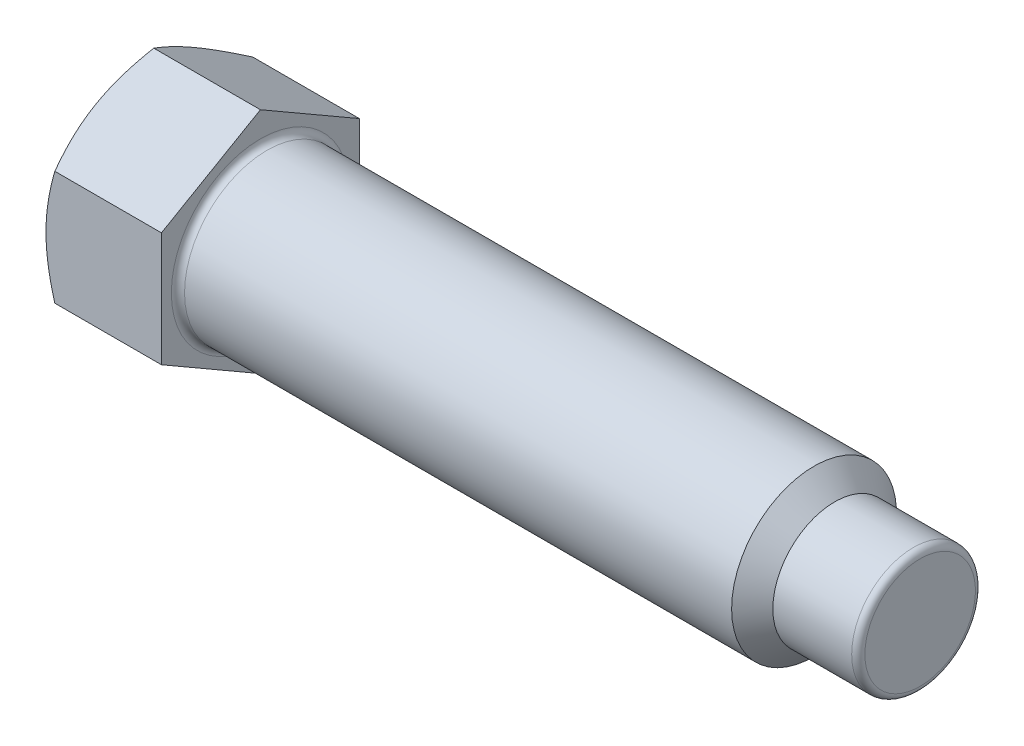
SolidWorks part; units mm, degrees
extrude "BaseHead" add sketch "HexSke" along normal blind 14
sketch "HexSke" plane through (0, 0, 0) normal (1, 0, 0) x (0, 0, -1)
  line L0 (12, 6.9282) -> (12, -6.9282)
  line L1 (-12, 6.9282) -> (-12, -6.9282)
  line L2 (12, -6.9282) -> (0, -13.8564)
  line L3 (0, -13.8564) -> (-12, -6.9282)
  line L4 (12, 6.9282) -> (0, 13.8564)
  line L5 (0, 13.8564) -> (-12, 6.9282)
  dimension "Width_flats" = 24
  dimension "D2" = 120
  dimension "D3" = 12
  dimension "D4" = 12
  dimension "D5" = 12
ref_plane "Plane1" through (0, 0, 0) normal (0, 0, 1) x (1, 0, 0)
ref_plane "Plane2" through (0, 0, 0) normal (0, 1, 0) x (1, 0, 0)
ref_plane "Plane3" through (0, 0, 0) normal (1, 0, 0) x (0, 0, -1)
sketch "BodySke" plane through (0, 0, 0) normal (0, 0, 1) x (1, 0, 0)
  line L0 (0, 6.9282) -> (0, -6.9282) construction
  line L1 (0, 0) -> (94, 0)
  line L2 (0, 0) -> (0, 10)
  line L3 (0, 10) -> (81.14, 10)
  line L4 (94, 0) -> (94, 7.5)
  line L5 (14, 13.8564) -> (14, 6.9282) construction
  line L6 (83.64, 7.5) -> (81.14, 10)
  line L7 (0, 0) -> (114.3068, 0) construction
  line L8 (128.3703, 17) -> (63.1669, 17) construction
  line L10 (16.5, 15.24) -> (16.5, -1.27) construction
  line L11 (94, 7.5) -> (83.64, 7.5)
  line L12 (14, 6.9282) -> (14, -6.9282) construction
  dimension "Body_ch_ang" = 45
  dimension "Diameter" = 20
  dimension "Minor_dia" = 17
revolve "BaseBody" add sketch "BodySke" angle 360 about L7
cosmetic thread "ThreadCosmetic" [suppressed] parameters "Thread_length"=67.14, "Thread_minor"=17
sketch "HeadChamSke" plane through (0, 0, 0) normal (0, 0, 1) x (1, 0, 0)
  line L0 (0, 12) -> (3.9585, 18.8564)
  line L1 (0, 13.8564) -> (0, 6.9282) construction
  line L2 (3.9585, 18.8564) -> (3.9585, 23.8564)
  line L3 (3.9585, 23.8564) -> (-10, 23.8564)
  line L4 (-10, 23.8564) -> (-10, 12)
  line L5 (-10, 12) -> (0, 12)
  line L6 (0, 0) -> (99.06, 0) construction
  line L7 (14, 13.8564) -> (0, 13.8564) construction
  dimension "D1" = 12
  dimension "D2" = 5
  dimension "D3" = 10
  dimension "D4" = 5
  dimension "Head_ch_ang" = 30
revolve "HeadChamfer" cut sketch "HeadChamSke" angle 360 about L6
fillet "HeadFillet" radius 0.8 1 edges at (14, 0, -10)
fillet "BaseBodyFillet" radius 0.8 1 edges at (94, 0, 7.5)
sketch "ThdSchSke" plane through (0, 0, 0) normal (0, 0, 1) x (1, 0, 0)
  line L0 (17.3, -8.5) -> (16.2497, -10)
  line L1 (17.3, -8.5) -> (18.3503, -10)
  line L2 (18.3503, -10) -> (18.3503, -12.5)
  line L3 (-3.175, 0) -> (5.1513, 0) construction
  line L5 (18.3503, -12.5) -> (16.2497, -12.5)
  line L6 (16.2497, -12.5) -> (16.2497, -10)
  dimension "Thread_minor" = 17
  dimension "Diameter" = 20
  dimension "Start" = 17.3
revolve "ThreadSchematic" [suppressed] cut sketch "ThdSchSke" angle 360 about L3
pattern_linear "ThdSchPat" [suppressed]
equation "\"D3@HexSke\" = \"Width_flats@HexSke\" / 2"
equation "\"D4@HexSke\" = \"D3@HexSke\""
equation "\"D5@HexSke\" = \"D4@HexSke\""
equation "\"Thread_minor@ThreadCosmetic\" = \"Minor_dia@BodySke\""
equation "\"D1@HeadChamSke\" = \"Width_flats@HexSke\" / 2"
equation "\"Thread_length@ThreadCosmetic\" = \"Length@BodySke\" - \"Dog_Lg@BodySke\" - \"Advance@BodySke\""
equation "\"Thread_minor@ThdSchSke\" = \"Minor_dia@BodySke\""
equation "\"Diameter@ThdSchSke\" = \"Diameter@BodySke\""
equation "\"Overcut@ThdSchSke\" = \"Diameter@BodySke\" * 1.25"
equation "\"Start@ThdSchSke\" = \"Fillet_Radius@HeadFillet\" + \"Advance@BodySke\" + \"Head_ht@BaseHead\""
equation "\"Num_threads@ThdSchPat\" = int( \"Thread_length@ThreadCosmetic\" / \"Advance@BodySke\" + 0.999 )  + 1"
equation "\"Advance@ThdSchPat\" = \"Thread_length@ThreadCosmetic\" /  (\"Num_threads@ThdSchPat\" - 1) 'relax it"
equation "\"Num_threads@ThdSchPat\" = \"Num_threads@ThdSchPat\" - sgn( \"Num_threads@ThdSchPat\" - 1) '---chamfered tips only---"
equation "\"Fillet_Radius@BaseBodyFillet\" = \"Fillet_Radius@HeadFillet\""
